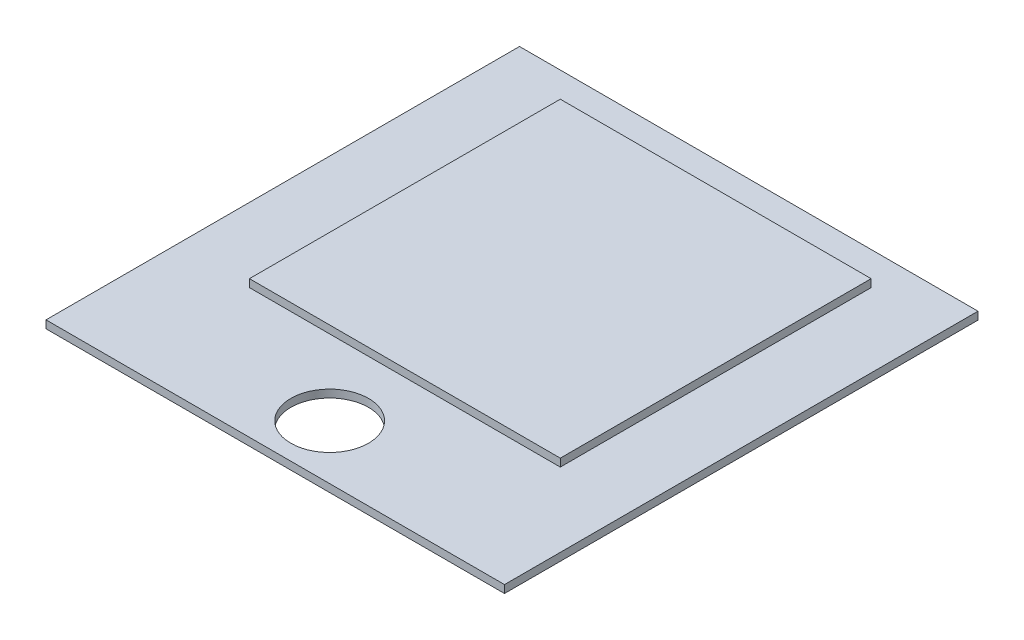
SolidWorks part; units mm, degrees
ref_plane "Front Plane" through (0, 0, 0) normal (0, 0, 1) x (1, 0, 0)
ref_plane "Top Plane" through (0, 0, 0) normal (0, 1, 0) x (1, 0, 0)
ref_plane "Right Plane" through (0, 0, 0) normal (1, 0, 0) x (0, 0, -1)
sketch "Sketch1" plane through (0, 0, 0) normal (0, 1, 0) x (1, 0, 0)
  line L1 (295, 304.65) -> (-295, 304.65)
  line L2 (295, 304.65) -> (295, -304.65)
  line L3 (295, -304.65) -> (-295, -304.65)
  line L4 (-295, 304.65) -> (-295, -304.65)
  line L5 (295, 304.65) -> (-295, -304.65) construction
  line L6 (295, -304.65) -> (-295, 304.65) construction
  point P0 (0, 0)
  dimension "D1" = 609.3
  dimension "D2" = 590
extrude "Boss-Extrude1" add sketch "Sketch1" along normal blind 10
sketch "Sketch3" plane through (0, 10, -62.2465) normal (0, 1, 0) x (1, 0, 0)
  line L0 (-3.7619, 242.4035) -> (-3.7619, 199.9035) construction
  line L1 (200, 199.9035) -> (-200, 199.9035)
  line L2 (200, 199.9035) -> (200, -200.0965)
  line L3 (200, -200.0965) -> (-200, -200.0965)
  line L4 (-200, 199.9035) -> (-200, -200.0965)
  line L5 (200, 199.9035) -> (-200, -200.0965) construction
  line L6 (200, -200.0965) -> (-200, 199.9035) construction
  line L8 (295, 242.4035) -> (-295, 242.4035) construction
  point P0 (0, -0.0965)
  dimension "D1" = 400
  dimension "D2" = 42.5
sketch "Sketch2" plane through (0, 10, 0) normal (0, 1, 0) x (1, 0, 0)
  line L0 (-295, -304.65) -> (295, -304.65) construction
  circle A1 centre (0, -234.65) radius 50
extrude "Cut-Extrude3" cut sketch "Sketch2" against normal through all
extrude "Boss-Extrude6" add sketch "Sketch3" along normal blind 10
equation "\"case_width\"= \"board_length\" + \"clock_width\" * 2 + \"clock_offset\" * 4"
equation "\"case_height\"= 100mm"
equation "\"609.3\"= 700mm"
equation "\"clock_width\"= 75mm"
equation "\"clock_length\"= 200mm"
equation "\"clock_height\"= 75mm"
equation "\"arm_offset\"= \"arm_sleeve_diameter\"/2 + 20"
equation "\"arm_sleeve_diameter\"= 100mm"
equation "\"square_length\"= 50mm"
